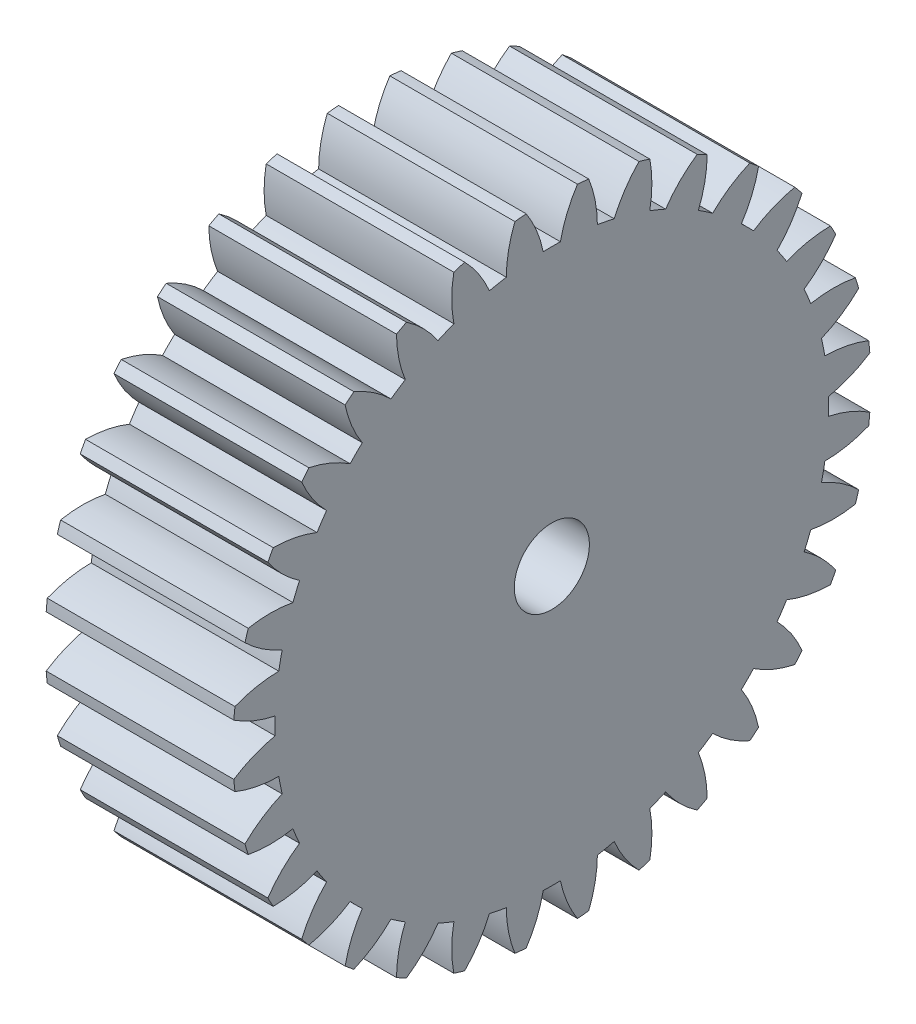
SolidWorks part; units mm, degrees
ref_plane "Plane1" through (0, 0, 0) normal (0, 0, 1) x (1, 0, 0)
ref_plane "Plane2" through (0, 0, 0) normal (0, 1, 0) x (1, 0, 0)
ref_plane "Plane3" through (0, 0, 0) normal (1, 0, 0) x (0, 0, -1)
sketch "HoldingSke" plane through (0, 0, 0) normal (0, 1, 0) x (1, 0, 0)
  line L0 (0, 0) -> (0.5654, -0.3533)
  line L1 (-15, 0) -> (100, 0) construction
  line L2 (0, 0) -> (-2.1039, 2.3779)
  line L3 (0, 0) -> (-11.863, 4.5341)
  line L4 (0, 0) -> (7.3237, 4.5764)
  line L5 (0, 0) -> (-46.8476, -17.4728)
  line L6 (0, 0) -> (-12.4344, -8.3896)
  line L7 (-2.1039, 2.3779) -> (8.6586, 51.2059)
  line L8 (-76.2, 54.61) -> (-75.2, 54.61)
  line L9 (-71.009, 38.7566) -> (-53.1078, 45.2721)
  line L10 (-76.2, 71.12) -> (104.1128, 71.12)
  line L11 (0, 0) -> (-15, 0)
  line L12 (-76.2, 101.6) -> (-76.147, 101.6)
  line L13 (24.9733, 27.94) -> (52.9518, 28.4284)
  line L14 (24.9733, 27.94) -> (24.9743, 27.94)
  line L15 (24.9733, 27.94) -> (100.4006, 29.5858)
  line L16 (-63.627, -1.5) -> (-12.827, -1.5)
  circle A0 centre (0, 0) radius 3
  circle A1 centre (0, 0) radius 22.124
  circle A2 centre (0, 0) radius 37.5
  circle A3 centre (0, 0) radius 3
  dimension "MHD" = 44.248
  dimension "Hub_dia" = 75
  dimension "Bore" = 6
  dimension "MBD" = 6
  dimension "Num_teeth" = 32
  dimension "Pitch" = 0.6667
  dimension "Overall_len" = 50
  dimension "Show_teeth" = 32
  dimension "Thickness" = 15
  dimension "OAL" = 50.0001
  dimension "T_dim" = 1
  dimension "Ap" = 20
  dimension "H" = 19.05
  dimension "Pitch_radius" = 180.3128
  dimension "Width" = 15
  dimension "Backlash" = 0.053
  dimension "Addendum_fac" = 1
  dimension "Dedendum_fac" = 1.25
  dimension "Clearance_fac" = 0.25
  dimension "Dedendum_add" = 0.001
  dimension "Module" = 1.5
sketch "BasProSke" plane through (0, 0, 0) normal (0, 1, 0) x (1, 0, 0)
  line L0 (-10, 0) -> (60, 0) construction
  line L1 (0, 0) -> (0, 25.5)
  line L2 (0, 0) -> (15, 0)
  line L3 (15, 0) -> (15, 25.5)
  line L4 (15, 25.5) -> (0, 25.5)
  dimension "Thickness" = 15
  dimension "Diameter" = 51
revolve "Base-Revolve" add sketch "BasProSke" angle 360 about L0
sketch "TooCutSke" plane through (0, 0, 0) normal (1, 0, 0) x (0, 0, -1)
  line L1 (0, 0) -> (0, 107) construction
  line L2 (0, 0) -> (-1.2704, 23.9664) construction
  line L3 (0, 0) -> (-4.7, 47.72) construction
  line L4 (-1.2704, 23.9664) -> (-2.35, 23.86) construction
  arc A0 (0.6867, 22.1133) -> (-0.6867, 22.1133) centre (0, 0) ccw
  arc A1 (2.0647, 25.4418) -> (-2.0647, 25.4418) centre (0, 0) ccw
  circle A2 centre (0, 0) radius 24 construction
  circle A3 centre (0, 0) radius 22.5526 construction
  arc A4 (-0.6867, 22.1133) -> (-2.0647, 25.4418) centre (-10.0881, 20.1706) ccw
  arc A5 (2.0647, 25.4418) -> (0.6867, 22.1133) centre (10.0881, 20.1706) ccw
  dimension "Root_dia" = 44.248
  dimension "Overcut_dia" = 51.0508
  dimension "Pitch_dia" = 48
  dimension "Base_dia" = 45.1052
  dimension "Flank_rad" = 9.6
  dimension "Half_ang" = 5.625
  dimension "Half_CT" = 1.0849
extrude "ToothCut" cut sketch "TooCutSke" along normal through all
fillet "Breaks" [suppressed] radius 0.03
fillet "RootFillets" [suppressed] radius 0.376
pattern_circular "TeethCuts" count 32 every 11.25 about axis through (-10, 0, 0) along (1, 0, 0) of "ToothCut", "RootFillets", "Breaks"
sketch "HubNeaOneSke" plane through (0, 0, 0) normal (-1, 0, 0) x (0, 0, 1)
  circle A0 centre (0, 0) radius 22.124
  dimension "Diameter" = 44.248
extrude "HubNearOne" [suppressed] add sketch "HubNeaOneSke" along normal blind 35.0001
sketch "HubNeaBotSke" plane through (0, 0, 0) normal (-1, 0, 0) x (0, 0, 1)
  circle A0 centre (0, 0) radius 22.124
  dimension "Diameter" = 44.248
extrude "HubNearBoth" [suppressed] add sketch "HubNeaBotSke" along normal blind 17.5
ref_plane "FarPln" through (15, 0, 0) normal (1, 0, 0) x (0, 0, -1)
sketch "HubFarSke" plane through (15, 0, 0) normal (1, 0, 0) x (0, 0, -1)
  circle A0 centre (0, 0) radius 22.124
  dimension "Diameter" = 44.248
extrude "HubFar" [suppressed] add sketch "HubFarSke" along normal blind 17.5
sketch "BorSke" plane through (0, 0, 0) normal (1, 0, 0) x (0, 0, -1)
  circle A0 centre (0, 0) radius 3
  dimension "Diameter" = 6
extrude "Bore" cut sketch "BorSke" along normal mid plane 100.0001
sketch "KeySke" plane through (0, 0, 0) normal (1, 0, 0) x (0, 0, -1)
  line L0 (-1, 0) -> (-1, 4)
  line L1 (-1, 4) -> (1, 4)
  line L2 (1, 4) -> (1, 0)
  line L3 (0, 0) -> (0, 34) construction
  line L4 (-1, 0) -> (1, 0)
  dimension "Offset" = 4
  dimension "Width" = 2
extrude "Keyway" [suppressed] cut sketch "KeySke" along normal mid plane 100.0001
pattern_circular "Keyway2" [suppressed] count 2 every 90 about axis through (-10, 0, 0) along (1, 0, 0)
equation "' \"Module@HoldingSke\" = 6.35"
equation "' \"Num_teeth@HoldingSke\" = 12"
equation "' \"Ap@HoldingSke\" =  20"
equation "' \"Ap@HoldingSke\" = 20"
equation "' \"Width@HoldingSke\" = 0.5 * 25.4"
equation "' \"Hub_dia@HoldingSke\"= 1 * 25.4"
equation "' \"Hub_dia@HoldingSke\" = 1 * 25.4"
equation "' \"Overall_len@HoldingSke\" = 1.0 * 25.4"
equation "' \"Bore@HoldingSke\" = 0.75 * 25.4"
equation "' \"T_dim@HoldingSke\" = 0.1 * 25.4"
equation "' \"Width@KeySke\" = 0.25 * 25.4"
equation "' \"Show_teeth@HoldingSke\" = 13"
equation "' \"Backlash@HoldingSke\" = 0.009 * 25.4"
equation "' \"Addendum_fac@HoldingSke\" = 1.0"
equation "' \"Dedendum_fac@HoldingSke\" = 1.25"
equation "' \"Dedendum_add@HoldingSke\" = 0.00005 * 25.4"
equation "' \"Clearance_fac@HoldingSke\" = 0.25"
equation "\"Pitch@HoldingSke\" = 1 / \"Module@HoldingSke\""
equation "\"Overcut_dia@TooCutSke\" = (\"Num_teeth@HoldingSke\" + 2 * \"Addendum_fac@HoldingSke\") / \"Pitch@HoldingSke\" + 0.002 * 25.4"
equation "\"Pitch_dia@TooCutSke\" = \"Num_teeth@HoldingSke\" / \"Pitch@HoldingSke\""
equation "\"Base_dia@TooCutSke\" = \"Num_teeth@HoldingSke\" / \"Pitch@HoldingSke\" * cos((\"Ap@HoldingSke\"  * 3.14159265 / 180))"
equation "\"Root_dia@TooCutSke\" = (\"Num_teeth@HoldingSke\" + 2) / \"Pitch@HoldingSke\" - 2 * (\"Addendum_fac@HoldingSke\" + \"Dedendum_fac@HoldingSke\") / \"Pitch@HoldingSke\" - \"Dedendum_add@HoldingSke\" * 2"
equation "\"Half_ang@TooCutSke\" = 180 / \"Num_teeth@HoldingSke\""
equation "\"Half_CT@TooCutSke\" = \"Num_teeth@HoldingSke\" / \"Pitch@HoldingSke\" * sin((3.14159265 / 2 / \"Num_teeth@HoldingSke\")) / 2 - 7 * \"Backlash@HoldingSke\" / 4"
equation "\"Flank_rad@TooCutSke\" = \"Num_teeth@HoldingSke\" / \"Pitch@HoldingSke\" / 5"
equation "\"Radius@RootFillets\" = \"Clearance_fac@HoldingSke\" / \"Pitch@HoldingSke\" + \"Dedendum_add@HoldingSke\""
equation "\"Break_rad@Breaks\" = 0.02 / \"Pitch@HoldingSke\""
equation "\"Thickness@HoldingSke\" = \"Width@HoldingSke\""
equation "\"OAL@HoldingSke\" = \"Thickness@HoldingSke\""
equation "\"MHD@HoldingSke\" = (\"Num_teeth@HoldingSke\" + 2) / \"Pitch@HoldingSke\" - 2 * (\"Addendum_fac@HoldingSke\" + \"Dedendum_fac@HoldingSke\")  / \"Pitch@HoldingSke\" - \"Dedendum_add@HoldingSke\" * 2"
equation "\"MBD@HoldingSke\" = (\"Num_teeth@HoldingSke\" + 2) / \"Pitch@HoldingSke\" - 2 * (\"Addendum_fac@HoldingSke\" + \"Dedendum_fac@HoldingSke\")  / \"Pitch@HoldingSke\" - \"Dedendum_add@HoldingSke\" * 2 - 0.002 * 25.4"
equation "\"MHD@HoldingSke\" = ((sgn( \"MHD@HoldingSke\" - \"Hub_dia@HoldingSke\" )-1)*( \"MHD@HoldingSke\" - \"Hub_dia@HoldingSke\" ))/-2+ \"Hub_dia@HoldingSke\""
equation "\"MBD@HoldingSke\" = ((sgn( \"MBD@HoldingSke\" - \"Bore@HoldingSke\" )-1)*( \"MBD@HoldingSke\" - \"Bore@HoldingSke\" ))/-2+ \"Bore@HoldingSke\""
equation "\"OAL@HoldingSke\" = ((sgn( \"OAL@HoldingSke\" - \"Overall_len@HoldingSke\" )+1)*( \"OAL@HoldingSke\" - \"Overall_len@HoldingSke\" ))/2 + \"Overall_len@HoldingSke\" + 0.000002 * 25.4"
equation "\"Num_teeth@TeethCuts\" = int( \"Show_teeth@HoldingSke\" ) + 1"
equation "\"Num_teeth@TeethCuts\" = ((sgn( \"Num_teeth@TeethCuts\" - \"Num_teeth@HoldingSke\" )-1)*( \"Num_teeth@TeethCuts\" - \"Num_teeth@HoldingSke\" ))/-2+ \"Num_teeth@HoldingSke\""
equation "\"Num_teeth@TeethCuts\" = ((sgn( \"Num_teeth@TeethCuts\" - 2.0)+1)*( \"Num_teeth@TeethCuts\" - 2.0))/2 +2.0"
equation "\"Angle@TeethCuts\" = 360.0 / \"Num_teeth@HoldingSke\""
equation "\"Diameter@BasProSke\" = (\"Num_teeth@HoldingSke\" + 2 * \"Addendum_fac@HoldingSke\") / \"Pitch@HoldingSke\""
equation "\"Thickness@BasProSke\"  = \"Thickness@HoldingSke\""
equation "' \"Fillet_rad@BasProSke\" =  \"Thickness@HoldingSke\" * 0.05"
equation "' \"Fillet_rad@BasProSke\" = \"Thickness@HoldingSke\" * 0.05"
equation "\"MHD@HoldingSke\" = ((sgn( \"MHD@HoldingSke\" - \"Root_dia@TooCutSke\" )-1)*( \"MHD@HoldingSke\" - \"Root_dia@TooCutSke\" ))/-2+ \"Root_dia@TooCutSke\""
equation "\"Diameter@HubNeaOneSke\" = \"MHD@HoldingSke\""
equation "\"Length@HubNearOne\" = \"OAL@HoldingSke\" - \"Thickness@BasProSke\""
equation "\"Diameter@HubNeaBotSke\" = \"MHD@HoldingSke\""
equation "\"Length@HubNearBoth\" = ( \"OAL@HoldingSke\" - \"Thickness@BasProSke\" ) / 2.0"
equation "\"Thickness@FarPln\" = \"Thickness@BasProSke\""
equation "\"Diameter@HubFarSke\" = \"MHD@HoldingSke\""
equation "\"Length@HubFar\" = ( \"OAL@HoldingSke\" - \"Thickness@BasProSke\" ) / 2.0"
equation "\"Diameter@BorSke\" = \"MBD@HoldingSke\""
equation "\"D1@Bore\" = \"OAL@HoldingSke\" * 2.0"
equation "\"D1@Keyway\" = \"OAL@HoldingSke\" * 2.0"
equation "\"Offset@KeySke\" = \"T_dim@HoldingSke\" + \"MBD@HoldingSke\" / 2.0"
